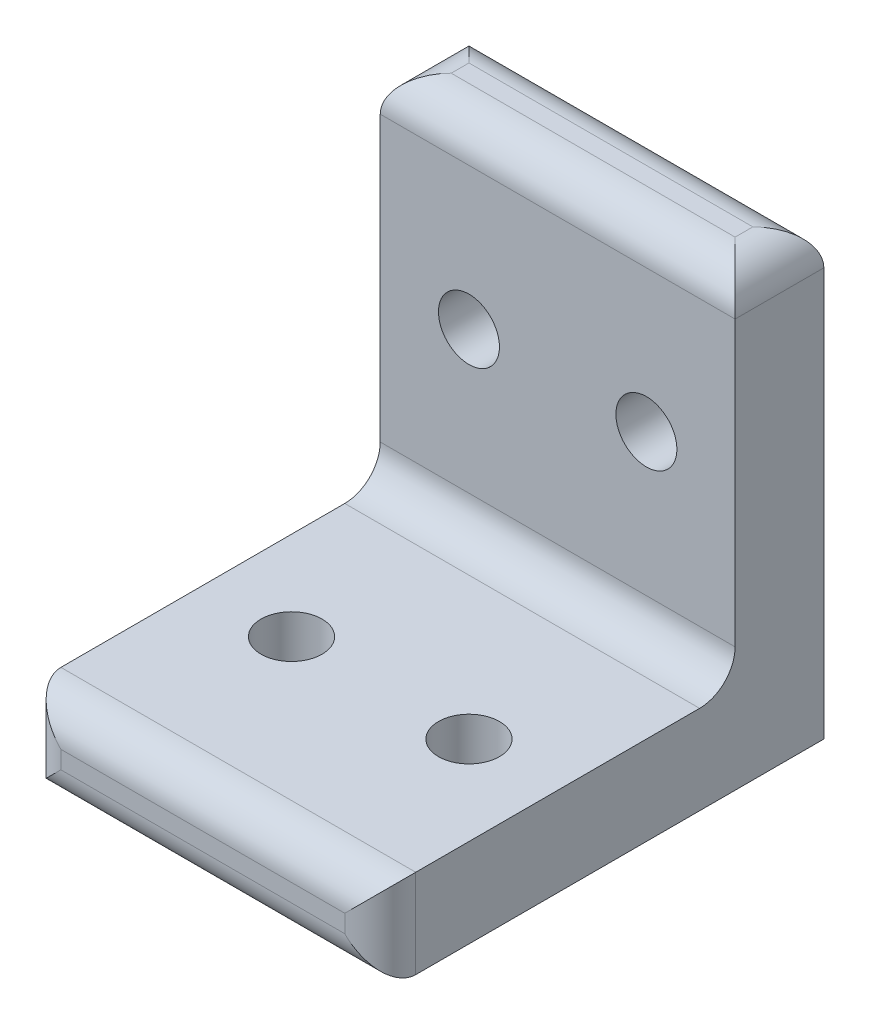
SolidWorks part; units mm, degrees
ref_plane "Front Plane" through (0, 0, 0) normal (0, 0, 1) x (1, 0, 0)
ref_plane "Top Plane" through (0, 0, 0) normal (0, 1, 0) x (1, 0, 0)
ref_plane "Right Plane" through (0, 0, 0) normal (1, 0, 0) x (0, 0, -1)
sketch "Sketch1" plane through (0, 0, 0) normal (0, 1, 0) x (1, 0, 0)
  line L1 (-12.7, -12.7) -> (12.7, -12.7)
  line L2 (-12.7, -12.7) -> (-12.7, 12.7)
  line L3 (-12.7, 12.7) -> (12.7, 12.7)
  line L4 (12.7, -12.7) -> (12.7, 12.7)
  line L5 (-12.7, -12.7) -> (12.7, 12.7) construction
  line L6 (-12.7, 12.7) -> (12.7, -12.7) construction
  point P0 (0, 0)
  dimension "D1" = 25.4
  dimension "D2" = 25.4
extrude "Boss-Extrude1" add sketch "Sketch1" along normal blind 6.35
sketch "Sketch2" plane through (0, 0, -12.7) normal (0, 0, -1) x (-1, 0, 0)
  line L1 (-12.7, 31.75) -> (12.7, 31.75)
  line L2 (-12.7, 31.75) -> (-12.7, 0)
  line L3 (-12.7, 0) -> (12.7, 0)
  line L4 (12.7, 31.75) -> (12.7, 0)
  line L5 (-12.7, 31.75) -> (12.7, 0) construction
  line L6 (-12.7, 0) -> (12.7, 31.75) construction
  point P0 (0, 15.875)
  dimension "D1" = 31.75
  dimension "D2" = 25.4
extrude "Boss-Extrude2" add sketch "Sketch2" along normal blind 6.35
fillet "Fillet1" radius 2.54 9 edges at (-12.7, 31.75, -15.875) (12.7, 31.75, -15.875) (-12.7, 3.175, 12.7) (12.7, 3.175, 12.7) (0, 31.75, -19.05) (0, 31.75, -12.7) (0, 0, 12.7) (0, 6.35, 12.7) (0, 6.35, -12.7)
sketch "Sketch3" plane through (0, 6.35, 0) normal (0, 1, 0) x (1, 0, 0)
  line L2 (-12.7, 10.16) -> (-12.7, -10.16) construction
  line L3 (12.7, -10.16) -> (12.7, 10.16) construction
  point P0 (-6.35, 0)
  point P1 (6.35, 0)
  dimension "D1" = 6.35
  dimension "D2" = 6.35
sketch "Sketch4" plane through (0, 0, -12.7) normal (0, 0, 1) x (1, 0, 0)
  line L0 (-12.7, 8.89) -> (12.7, 8.89) construction
  line L1 (-12.7, 8.89) -> (-12.7, 29.21) construction
  line L2 (12.7, 29.21) -> (12.7, 8.89) construction
  point P0 (6.35, 19.05)
  point P3 (-6.35, 19.05)
  dimension "D1" = 10.16
  dimension "D2" = 6.35
  dimension "D3" = 6.35
hole_wizard "11/64 (0.17188) Diameter Hole1" positions "Sketch5" profile "Sketch6" hole size "11/64" standard "ANSI Inch" end condition through all
sketch "Sketch5" plane through (0, 6.35, 0) normal (0, 1, 0) x (1, 0, 0)
  point P3 (-6.35, 0)
  point P6 (6.35, 0)
sketch "Sketch6" plane through (-6.35, 6.35, 0) normal (1, 0, 0) x (0, 0, 1)
  line L0 (0, 0) -> (0, 6.35)
  line L1 (0, 6.35) -> (2.1829, 6.35)
  line L2 (2.1829, 6.35) -> (2.1829, 0)
  line L5 (2.1829, 0) -> (0, 0)
  line L11 (0, -6.35) -> (0, 107.95) construction
  dimension "Thru Hole Dia." = 4.3658
  dimension "Thru Hole Depth" = 6.35
hole_wizard "11/64 (0.17188) Diameter Hole2" positions "Sketch7" profile "Sketch8" hole size "11/64" standard "ANSI Inch" end condition through all
sketch "Sketch7" plane through (0, 0, -12.7) normal (0, 0, 1) x (1, 0, 0)
  point P0 (6.35, 19.05)
  point P3 (-6.35, 19.05)
sketch "Sketch8" plane through (6.35, 19.05, -12.7) normal (1, 0, 0) x (0, -1, 0)
  line L0 (0, 0) -> (0, 6.35)
  line L1 (0, 6.35) -> (2.1829, 6.35)
  line L2 (2.1829, 6.35) -> (2.1829, 0)
  line L5 (2.1829, 0) -> (0, 0)
  line L11 (0, -6.35) -> (0, 107.95) construction
  dimension "Thru Hole Dia." = 4.3658
  dimension "Thru Hole Depth" = 6.35
